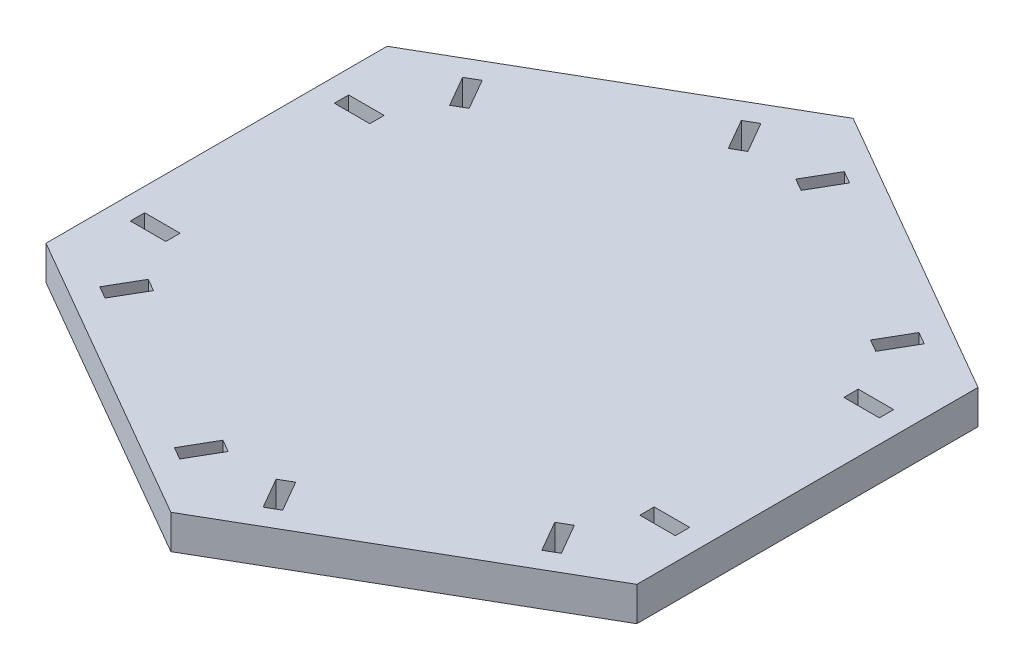
SolidWorks part; units mm, degrees
ref_plane "Front Plane" through (0, 0, 0) normal (0, 0, 1) x (1, 0, 0)
ref_plane "Top Plane" through (0, 0, 0) normal (0, 1, 0) x (1, 0, 0)
ref_plane "Right Plane" through (0, 0, 0) normal (1, 0, 0) x (0, 0, -1)
sketch "Sketch1" plane through (0, 0, 0) normal (0, 1, 0) x (1, 0, 0)
  line L0 (-43.9941, 25.4) -> (0, 0) construction
  line L1 (43.9941, 25.4) -> (0, 50.8)
  line L2 (0, 50.8) -> (-43.9941, 25.4)
  line L3 (-43.9941, 25.4) -> (-43.9941, -25.4)
  line L4 (-43.9941, -25.4) -> (0, -50.8)
  line L5 (0, -50.8) -> (43.9941, -25.4)
  line L6 (43.9941, -25.4) -> (43.9941, 25.4)
  line L7 (-42.9616, 33.7684) -> (-39.6596, 28.0492)
  line L8 (-50.7251, 17.6546) -> (-44.1211, 17.6546)
  line L9 (-50.7251, 17.6546) -> (-50.7251, 20.3216)
  line L10 (-50.7251, 20.3216) -> (-44.1211, 20.3216)
  line L11 (-44.1211, 17.6546) -> (-44.1211, 20.3216)
  line L12 (-50.7251, 17.6546) -> (-44.1211, 20.3216) construction
  line L13 (-50.7251, 20.3216) -> (-44.1211, 17.6546) construction
  line L14 (54.9926, 31.75) -> (0, 63.5)
  line L15 (0, 63.5) -> (-54.9926, 31.75)
  line L16 (-54.9926, 31.75) -> (-54.9926, -31.75)
  line L17 (-54.9926, -31.75) -> (0, -63.5)
  line L18 (0, -63.5) -> (54.9926, -31.75)
  line L19 (54.9926, -31.75) -> (54.9926, 31.75)
  line L20 (-37.3499, 29.3827) -> (-39.6596, 28.0492)
  line L21 (-40.6519, 35.1019) -> (-37.3499, 29.3827)
  line L22 (-40.6519, 35.1019) -> (-42.9616, 33.7684)
  line L23 (-10.0732, 52.7565) -> (-7.7635, 54.09)
  line L24 (-10.0732, 52.7565) -> (-6.7712, 47.0373)
  line L25 (-6.7712, 47.0373) -> (-4.4615, 48.3708)
  line L26 (-7.7635, 54.09) -> (-4.4615, 48.3708)
  line L27 (7.7635, 54.09) -> (4.4615, 48.3708)
  line L28 (6.7712, 47.0373) -> (4.4615, 48.3708)
  line L29 (10.0732, 52.7565) -> (6.7712, 47.0373)
  line L30 (10.0732, 52.7565) -> (7.7635, 54.09)
  line L31 (40.6519, 35.1019) -> (42.9616, 33.7684)
  line L32 (40.6519, 35.1019) -> (37.3499, 29.3827)
  line L33 (37.3499, 29.3827) -> (39.6596, 28.0492)
  line L34 (42.9616, 33.7684) -> (39.6596, 28.0492)
  line L35 (50.7251, 20.3216) -> (44.1211, 20.3216)
  line L36 (44.1211, 17.6546) -> (44.1211, 20.3216)
  line L37 (50.7251, 17.6546) -> (44.1211, 17.6546)
  line L38 (50.7251, 17.6546) -> (50.7251, 20.3216)
  line L39 (50.7251, -17.6546) -> (50.7251, -20.3216)
  line L40 (50.7251, -17.6546) -> (44.1211, -17.6546)
  line L41 (44.1211, -17.6546) -> (44.1211, -20.3216)
  line L42 (50.7251, -20.3216) -> (44.1211, -20.3216)
  line L43 (42.9616, -33.7684) -> (39.6596, -28.0492)
  line L44 (37.3499, -29.3827) -> (39.6596, -28.0492)
  line L45 (40.6519, -35.1019) -> (37.3499, -29.3827)
  line L46 (40.6519, -35.1019) -> (42.9616, -33.7684)
  line L47 (10.0732, -52.7565) -> (7.7635, -54.09)
  line L48 (10.0732, -52.7565) -> (6.7712, -47.0373)
  line L49 (6.7712, -47.0373) -> (4.4615, -48.3708)
  line L50 (7.7635, -54.09) -> (4.4615, -48.3708)
  line L51 (-7.7635, -54.09) -> (-4.4615, -48.3708)
  line L52 (-6.7712, -47.0373) -> (-4.4615, -48.3708)
  line L53 (-10.0732, -52.7565) -> (-6.7712, -47.0373)
  line L54 (-10.0732, -52.7565) -> (-7.7635, -54.09)
  line L55 (-40.6519, -35.1019) -> (-42.9616, -33.7684)
  line L56 (-40.6519, -35.1019) -> (-37.3499, -29.3827)
  line L57 (-37.3499, -29.3827) -> (-39.6596, -28.0492)
  line L58 (-42.9616, -33.7684) -> (-39.6596, -28.0492)
  line L59 (-50.7251, -20.3216) -> (-44.1211, -20.3216)
  line L60 (-44.1211, -17.6546) -> (-44.1211, -20.3216)
  line L61 (-50.7251, -17.6546) -> (-44.1211, -17.6546)
  line L62 (-50.7251, -17.6546) -> (-50.7251, -20.3216)
  circle A0 centre (0, 0) radius 43.9941 construction
  circle A1 centre (0, 0) radius 54.9926 construction
  circle A2 centre (0, 0) radius 43.9941 construction
  circle A3 centre (0, 0) radius 43.9941 construction
  circle A4 centre (0, 0) radius 43.9941 construction
  circle A5 centre (0, 0) radius 43.9941 construction
  circle A6 centre (0, 0) radius 43.9941 construction
  circle A7 centre (0, 0) radius 1.27
  point P1 (-47.4231, 18.9881)
  point P73 (0, 0)
  dimension "D9" = 2.54
  dimension "D1" = 50.8
  dimension "D2" = 101.6
  dimension "D3" = 2.667
  dimension "D4" = 6.604
  dimension "D5" = 5.08
  dimension "D6" = 3.429
  dimension "D7" = 12.7
  dimension "D8" = 6
extrude "Boss-Extrude1" add sketch "Sketch1" along normal blind 6.35 contours L3 L61 L60 L59 L4 L58 L57 L56 L53 L52 L51 L5 L50 L49 L48 L45 L44 L43 L6 L42 L41 L40 L37 L36 L35 L1 L34 L33 L32 L29 L28 L27 L2 L26 L25 L24 L21 L20 L7 | L18 L19 L14 L15 L16 L17 L6 L5 L4 L3 L2 L1
sketch "Sketch2" plane through (0, 6.35, 0) normal (0, 1, 0) x (1, 0, 0)
  text T0 "PAULINA" font "Century Gothic" height 3.5
